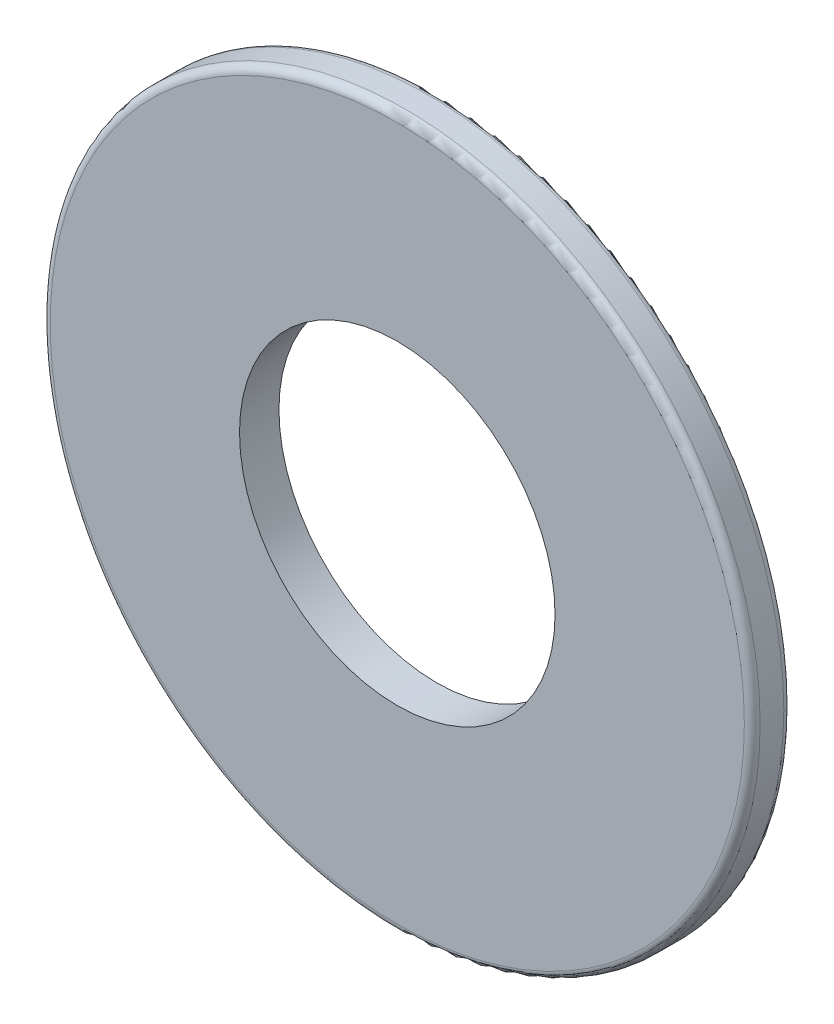
SolidWorks part; units mm, degrees
ref_plane "Front Plane" through (0, 0, 0) normal (0, 0, 1) x (1, 0, 0)
ref_plane "Top Plane" through (0, 0, 0) normal (0, 1, 0) x (1, 0, 0)
ref_plane "Right Plane" through (0, 0, 0) normal (1, 0, 0) x (0, 0, -1)
sketch "Esquisse1" plane through (0, 0, 0) normal (0, 0, 1) x (1, 0, 0)
  circle A0 centre (0, 0) radius 2
  circle A1 centre (0, 0) radius 4.5
  dimension "D1" = 4
  dimension "D2" = 9
extrude "Boss.-Extru.1" add sketch "Esquisse1" along normal blind 0.5
fillet "Congé1" radius 0.1 2 edges at (4.5, 0, 0) (4.5, 0, 0.5)
